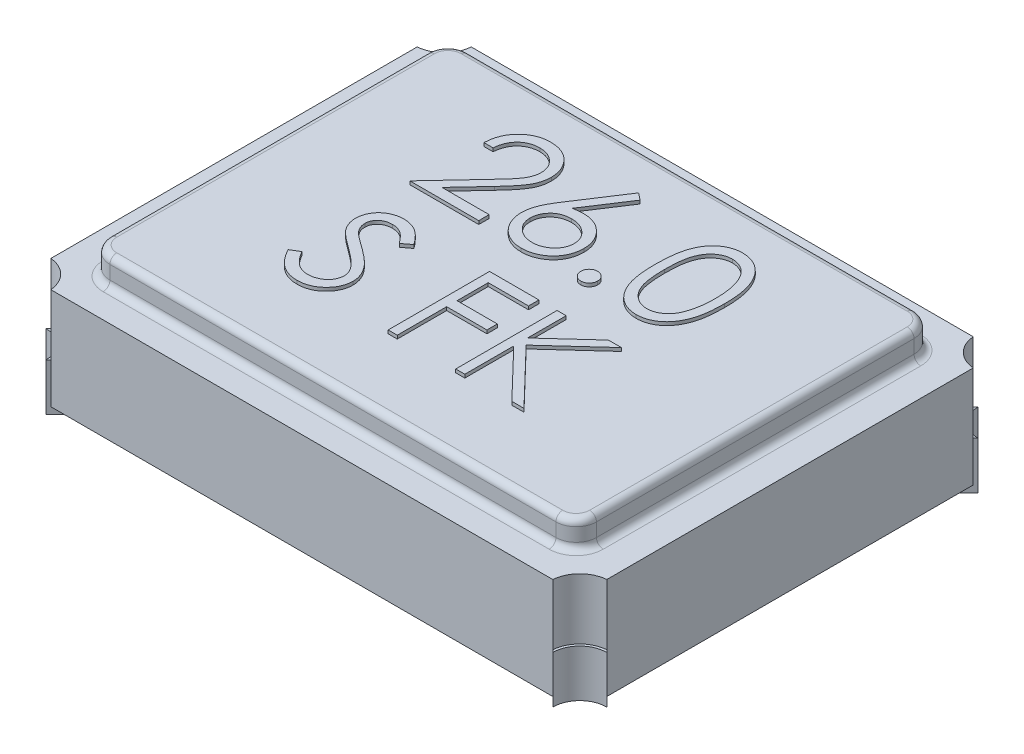
SolidWorks part; units mm, degrees
ref_plane "Спереди" through (0, 0, 0) normal (0, 0, 1) x (1, 0, 0)
ref_plane "Сверху" through (0, 0, 0) normal (0, 1, 0) x (1, 0, 0)
ref_plane "Справа" through (0, 0, 0) normal (1, 0, 0) x (0, 0, -1)
sketch "Эскиз2" plane through (0, 0, 0) normal (0, 1, 0) x (1, 0, 0)
  line L0 (-1.1089, 0) -> (1.2282, 0) construction
  line L1 (0, 0) -> (0, 1.0852) construction
  line L2 (0.83, -0.6293) -> (-0.83, -0.6293) construction
  line L3 (0.83, -0.6293) -> (0.83, 0.6293) construction
  line L4 (0.83, 0.6293) -> (-0.83, 0.6293) construction
  line L5 (-0.83, -0.6293) -> (-0.83, 0.6293) construction
  line L6 (0.83, -0.6293) -> (-0.83, 0.6293) construction
  line L7 (0.83, 0.6293) -> (-0.83, -0.6293) construction
  line L8 (0, 0) -> (0, -1.3812) construction
  line L9 (-0.83, 0.5493) -> (0.83, 0.5493) construction
  line L10 (-0.83, 0.5493) -> (-0.75, 0.6293) construction
  line L11 (-0.2644, 0.1567) -> (-0.745, 0.1567) construction
  line L12 (-0.2644, 0.1567) -> (-0.2644, 0.5414) construction
  line L13 (-0.2644, 0.5414) -> (-0.745, 0.5414) construction
  line L14 (-0.2644, -0.6354) -> (0.2619, -0.6247) construction
  line L15 (-0.2644, -0.6354) -> (-0.2644, 0.6307) construction
  line L16 (-0.2644, 0.6307) -> (0.2619, 0.6293) construction
  line L17 (0.2619, -0.6247) -> (0.2619, 0.6293) construction
  line L18 (-0.2644, -0.6354) -> (0.2619, 0.6293) construction
  line L19 (-0.2644, 0.6307) -> (0.2619, -0.6247) construction
  line L20 (-0.83, 0.1567) -> (0.8302, 0.1567) construction
  line L21 (-0.83, 0.1567) -> (-0.8302, -0.1567) construction
  line L22 (-0.8302, -0.1567) -> (0.83, -0.1567) construction
  line L23 (0.8302, 0.1567) -> (0.83, -0.1567) construction
  line L24 (-0.83, 0.1567) -> (0.83, -0.1567) construction
  line L25 (-0.8302, -0.1567) -> (0.8302, 0.1567) construction
  line L26 (-0.83, -0.5493) -> (0.83, -0.5493) construction
  line L27 (-0.745, 0.1567) -> (-0.745, 0.5414) construction
  line L28 (-0.83, 0.5493) -> (-0.742, 0.4614) construction
  line L29 (-0.75, 0.6293) -> (-0.662, 0.5414) construction
  line L30 (-0.742, 0.4614) -> (-0.662, 0.5414) construction
  line L31 (-0.2644, 0.1567) -> (-0.745, 0.1567) construction
  line L32 (-0.745, 0.1567) -> (-0.745, 0.4643)
  line L33 (-0.745, 0.4643) -> (-0.83, 0.5493)
  line L34 (-0.2644, 0.1567) -> (-0.2644, 0.5414) construction
  line L35 (-0.2644, 0.5414) -> (-0.662, 0.5414)
  line L36 (-0.75, 0.6293) -> (-0.662, 0.5414)
  line L37 (0.75, 0.6293) -> (0.662, 0.5414)
  line L38 (0.745, 0.4643) -> (0.83, 0.5493)
  line L39 (0.745, 0.1567) -> (0.745, 0.4643)
  line L40 (0.2644, 0.1567) -> (0.745, 0.1567)
  line L41 (0.2644, 0.1567) -> (0.2644, 0.5414)
  line L42 (0.2644, 0.5414) -> (0.662, 0.5414)
  line L43 (-0.75, -0.6293) -> (-0.662, -0.5414)
  line L44 (-0.745, -0.4643) -> (-0.83, -0.5493)
  line L45 (-0.745, -0.1567) -> (-0.745, -0.4643)
  line L46 (-0.2644, -0.5414) -> (-0.662, -0.5414)
  line L47 (-0.2644, -0.1567) -> (-0.2644, -0.5414)
  line L48 (-0.2644, -0.1567) -> (-0.745, -0.1567)
  line L49 (0.2644, -0.1567) -> (0.2644, -0.5414)
  line L50 (0.2644, -0.5414) -> (0.662, -0.5414)
  line L51 (0.75, -0.6293) -> (0.662, -0.5414)
  line L52 (0.745, -0.4643) -> (0.83, -0.5493)
  line L53 (0.745, -0.1567) -> (0.745, -0.4643)
  line L54 (0.2644, -0.1567) -> (0.745, -0.1567)
  line L55 (-0.2644, 0.5414) -> (-0.2644, 0.3314)
  line L56 (-0.2644, 0.3314) -> (-0.4392, 0.1567)
  line L57 (-0.4392, 0.1567) -> (-0.745, 0.1567)
  circle A0 centre (-0.83, 0.6293) radius 0.08 construction
  circle A1 centre (-0.83, -0.6293) radius 0.08 construction
  circle A2 centre (0.83, -0.6293) radius 0.08 construction
  circle A3 centre (0.83, 0.6293) radius 0.08 construction
  arc A4 (-0.83, 0.5493) -> (-0.75, 0.6293) centre (-0.83, 0.6293) ccw
  arc A5 (0.83, 0.5493) -> (0.75, 0.6293) centre (0.83, 0.6293) cw
  arc A6 (-0.83, -0.5493) -> (-0.75, -0.6293) centre (-0.83, -0.6293) cw
  arc A7 (0.83, -0.5493) -> (0.75, -0.6293) centre (0.83, -0.6293) ccw
  point P2 (0, 0)
extrude "Бобышка-Вытянуть2" add sketch "Эскиз2" along normal blind 0.02
ref_plane "Плоскость1" through (0, 0.02, 0) normal (0, 1, 0) x (-1, 0, 0)
sketch "Эскиз5" plane through (0, 0.02, 0) normal (0, 1, 0) x (-1, 0, 0)
  line L0 (0, -0.8137) -> (0, 0.8285) construction
  line L1 (0.9756, 0) -> (-1.114, 0) construction
  line L2 (0.75, -0.6293) -> (0.7429, -0.6223)
  line L3 (0.662, -0.5414) -> (0.75, -0.6293) construction
  line L4 (-0.83, -0.5493) -> (-0.8229, -0.5423)
  line L5 (0.83, -0.5493) -> (0.8229, -0.5423)
  line L6 (0.83, -0.5493) -> (0.745, -0.4643) construction
  line L7 (-0.75, -0.6293) -> (-0.7429, -0.6223)
  line L8 (-0.75, 0.6293) -> (-0.7429, 0.6223)
  line L9 (0.83, 0.5493) -> (0.8229, 0.5423)
  line L10 (-0.83, 0.5493) -> (-0.8229, 0.5423)
  line L11 (0.75, 0.6293) -> (0.7429, 0.6223)
  arc A0 (0.8229, -0.5423) -> (0.7429, -0.6223) centre (0.83, -0.6293) ccw
  arc A1 (0.83, -0.5493) -> (0.75, -0.6293) centre (0.83, -0.6293) ccw
  arc A2 (-0.83, -0.5493) -> (-0.75, -0.6293) centre (-0.83, -0.6293) cw
  arc A3 (-0.8229, -0.5423) -> (-0.7429, -0.6223) centre (-0.83, -0.6293) cw
  arc A4 (-0.8229, 0.5423) -> (-0.7429, 0.6223) centre (-0.83, 0.6293) ccw
  arc A5 (-0.83, 0.5493) -> (-0.75, 0.6293) centre (-0.83, 0.6293) ccw
  arc A6 (0.83, 0.5493) -> (0.75, 0.6293) centre (0.83, 0.6293) cw
  arc A7 (0.8229, 0.5423) -> (0.7429, 0.6223) centre (0.83, 0.6293) cw
extrude "Бобышка-Вытянуть4" add sketch "Эскиз5" along normal blind 0.12
sketch "Эскиз6" plane through (0, 0.02, 0) normal (0, 1, 0) x (-1, 0, 0)
  line L0 (0.8229, -0.5423) -> (0.8229, 0.5423)
  line L1 (0.7429, 0.6223) -> (-0.7429, 0.6223)
  line L2 (-0.8229, 0.5423) -> (-0.8229, -0.5423)
  line L3 (-0.7429, -0.6223) -> (0.7429, -0.6223)
  arc A0 (0.8229, 0.5423) -> (0.7429, 0.6223) centre (0.83, 0.6293) cw
  arc A1 (-0.7429, 0.6223) -> (-0.8229, 0.5423) centre (-0.83, 0.6293) cw
  arc A2 (-0.8229, -0.5423) -> (-0.7429, -0.6223) centre (-0.83, -0.6293) cw
  arc A3 (0.7429, -0.6223) -> (0.8229, -0.5423) centre (0.83, -0.6293) cw
extrude "Бобышка-Вытянуть8" add sketch "Эскиз6" along normal blind 0.3
ref_plane "Плоскость3" through (0, 0.32, 0) normal (0, 1, 0) x (-1, 0, 0)
sketch "Эскиз7" plane through (0, 0.32, 0) normal (0, 1, 0) x (-1, 0, 0)
  line L1 (-0.72, 0.53) -> (0.72, 0.53)
  line L2 (-0.72, 0.53) -> (-0.72, -0.53)
  line L3 (-0.72, -0.53) -> (0.72, -0.53)
  line L4 (0.72, 0.53) -> (0.72, -0.53)
  line L5 (-0.72, 0.53) -> (0.72, -0.53) construction
  line L6 (-0.72, -0.53) -> (0.72, 0.53) construction
  point P0 (0, 0)
extrude "Бобышка-Вытянуть9" add sketch "Эскиз7" along normal blind 0.08
sketch "Эскиз8" plane through (0, 0.4, 0) normal (0, 1, 0) x (-1, 0, 0)
  line L0 (0.4119, 0.3161) -> (-0.5448, 0.3161) construction
  line L1 (0.4119, -0.0981) -> (-0.4541, -0.0981) construction
  text T0 "S FK" font "Century Gothic" height 0.3
  text T1 "26.0" font "Century Gothic" height 0.3
fillet "Скругление3" radius 0.06 4 edges at (0.72, 0.36, -0.53) (0.72, 0.36, 0.53) (-0.72, 0.36, -0.53) (-0.72, 0.36, 0.53)
fillet "Скругление4" radius 0.02 8 edges at (0.7024, 0.4, 0.5124) (0, 0.4, 0.53) (-0.7024, 0.4, 0.5124) (-0.72, 0.4, 0) (-0.7024, 0.4, -0.5124) (0, 0.4, -0.53) (0.7024, 0.4, -0.5124) (0.72, 0.4, 0)
fillet "Скругление5" radius 0.02 8 edges at (-0.7024, 0.32, 0.5124) (-0.72, 0.32, 0) (-0.7024, 0.32, -0.5124) (0, 0.32, -0.53) (0.7024, 0.32, -0.5124) (0.72, 0.32, 0) (0.7024, 0.32, 0.5124) (0, 0.32, 0.53)
extrude "Бобышка-Вытянуть10" add sketch "Эскиз8" along normal blind 0.01
